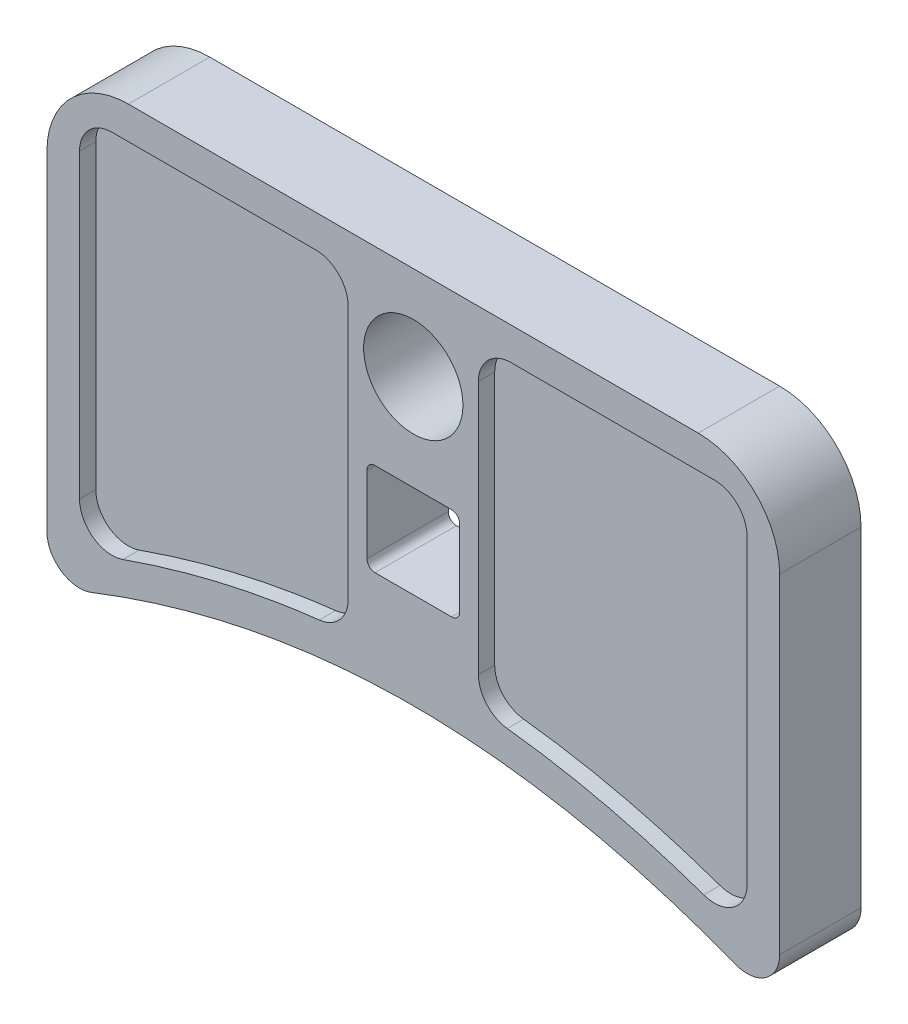
SolidWorks part; units mm, degrees
material "ABS"
ref_plane "Front Plane" through (0, 0, 0) normal (0, 0, 1) x (1, 0, 0)
ref_plane "Top Plane" through (0, 0, 0) normal (0, 1, 0) x (1, 0, 0)
ref_plane "Right Plane" through (0, 0, 0) normal (1, 0, 0) x (0, 0, -1)
sketch "Sketch1" plane through (0, 0, 0) normal (0, 0, 1) x (1, 0, 0)
  line L0 (-22.5, -11.625) -> (-22.5, -16.625)
  line L1 (-22.5, 11.625) -> (22.5, 11.625)
  line L2 (-22.5, 11.625) -> (-22.5, -11.625)
  line L3 (-22.5, -11.625) -> (22.5, -11.625) construction
  line L4 (22.5, 11.625) -> (22.5, -11.625)
  line L5 (-22.5, 11.625) -> (22.5, -11.625) construction
  line L6 (-22.5, -11.625) -> (22.5, 11.625) construction
  line L7 (22.5, -11.625) -> (22.5, -16.625)
  spline S0 degree 2 poles (-22.5, -16.625) (0, -6.625) (22.5, -16.625) knots 0 0 0 1 1 1
  point P0 (0, 0)
  dimension "D1" = 23.25
  dimension "D2" = 45
  dimension "D3" = 5
extrude "Boss-Extrude1" add sketch "Sketch1" against normal blind 5
sketch "Sketch2" plane through (0, 0, 0) normal (0, 0, 1) x (1, 0, 0)
  line L0 (0, 11.625) -> (0, -11.625) construction
  line L4 (22.5, 11.625) -> (-22.5, 11.625) construction
  line L5 (-2.85, -0.025) -> (2.85, -0.025)
  line L6 (-2.85, -0.025) -> (-2.85, -5.725)
  line L7 (-2.85, -5.725) -> (2.85, -5.725)
  line L8 (2.85, -0.025) -> (2.85, -5.725)
  line L9 (-2.85, -0.025) -> (2.85, -5.725) construction
  line L10 (-2.85, -5.725) -> (2.85, -0.025) construction
  line L11 (22.5, -16.625) -> (22.5, 11.625) construction
  line L14 (22.5, 11.625) -> (-22.5, 11.625) construction
  circle A0 centre (0, 5.875) radius 3.05
  parabola Q5 (-22.5, -16.625) -> (22.5, -16.625) focus (0, -36.9375) apex (0, -11.625) construction
  point P10 (0, -2.875)
  dimension "D2" = 6.1
  dimension "D1" = 8.75
  dimension "D3" = 5.7
  dimension "D4" = 5.75
  dimension "D5" = 8.75
  dimension "D7" = 19.65
extrude "Cut-Extrude1" cut sketch "Sketch2" against normal through all
fillet "Fillet1" radius 0.5 4 edges at (2.85, -5.725, -2.5) (-2.85, -5.725, -2.5) (-2.85, -0.025, -2.5) (2.85, -0.025, -2.5)
ref_plane "Plane1" through (0, -2.875, 0) normal (0, -1, 0) x (-1, 0, 0)
sketch "Sketch3" plane through (0, 0, 0) normal (0, 0, 1) x (1, 0, 0)
  line L0 (0, 11.625) -> (0, -11.625) construction
  line L1 (22.5, 11.625) -> (-22.5, 11.625) construction
  line L2 (-20.5, 9.625) -> (-20.5, -13.7756)
  line L3 (22.5, -16.625) -> (22.5, 11.625) construction
  line L4 (4, 9.625) -> (4, -9.783)
  line L5 (4, 9.625) -> (20.5, 9.625)
  line L6 (20.5, 9.625) -> (20.5, -13.7756)
  line L8 (-22.5, 11.625) -> (-22.5, -16.625) construction
  line L10 (-22.5, -14.625) -> (22.5, -14.625) construction
  line L11 (-4, 9.625) -> (-20.5, 9.625)
  line L12 (-4, 9.625) -> (-4, -9.783)
  parabola Q0 (-22.5, -16.625) -> (22.5, -16.625) focus (0, -36.9375) apex (0, -11.625) construction
  spline S0 degree 3 poles (4, -9.783) (9.5, -10.2176) (15, -11.5485) (20.5, -13.7756) knots 0.588889 0.588889 0.588889 0.588889 0.955556 0.955556 0.955556 0.955556
  spline S1 degree 2 poles (-22.5, -14.625) (-11.25, -9.625) (0, -9.625) knots 0 0 0 0.5 0.5 0.5 construction
  spline S2 degree 3 poles (0, -9.625) (1.3333, -9.625) (2.6667, -9.6777) (4, -9.783) knots 0.5 0.5 0.5 0.5 0.588889 0.588889 0.588889 0.588889 construction
  spline S3 degree 2 poles (20.5, -13.7756) (21.5, -14.1806) (22.5, -14.625) knots 0.955556 0.955556 0.955556 1 1 1 construction
  spline S4 degree 2 poles (-20.5, -13.7756) (-21.5, -14.1806) (-22.5, -14.625) knots 0.955556 0.955556 0.955556 1 1 1 construction
  spline S5 degree 3 poles (-4, -9.783) (-9.5, -10.2176) (-15, -11.5485) (-20.5, -13.7756) knots 0.588889 0.588889 0.588889 0.588889 0.955556 0.955556 0.955556 0.955556
  point P8 (0, -9.625)
  point P9 (-22.5, -14.625)
  point P10 (22.5, -14.625)
  point P28 (-22.5, -14.625)
  dimension "D3" = 2
  dimension "D4" = 2
  dimension "D5" = 5
  dimension "D2" = 4
  dimension "D1" = 2
  dimension "D6" = 16.5
  dimension "D7" = 19.408
  dimension "D8" = 23.4006
  dimension "D9" = 45
extrude "Cut-Extrude2" cut sketch "Sketch3" against normal blind 1
fillet "Fillet2" radius 5 2 edges at (22.5, 11.625, -2.5) (-22.5, 11.625, -2.5)
fillet "Fillet3" radius 2 2 edges at (22.5, -16.625, -2.5) (-22.5, -16.625, -2.5)
fillet "Fillet4" radius 2 8 edges at (20.5, -13.7756, -0.5) (4, -9.783, -0.5) (20.5, 9.625, -0.5) (4, 9.625, -0.5) (-4, 9.625, -0.5) (-20.5, 9.625, -0.5) (-4, -9.783, -0.5) (-20.5, -13.7756, -0.5)
